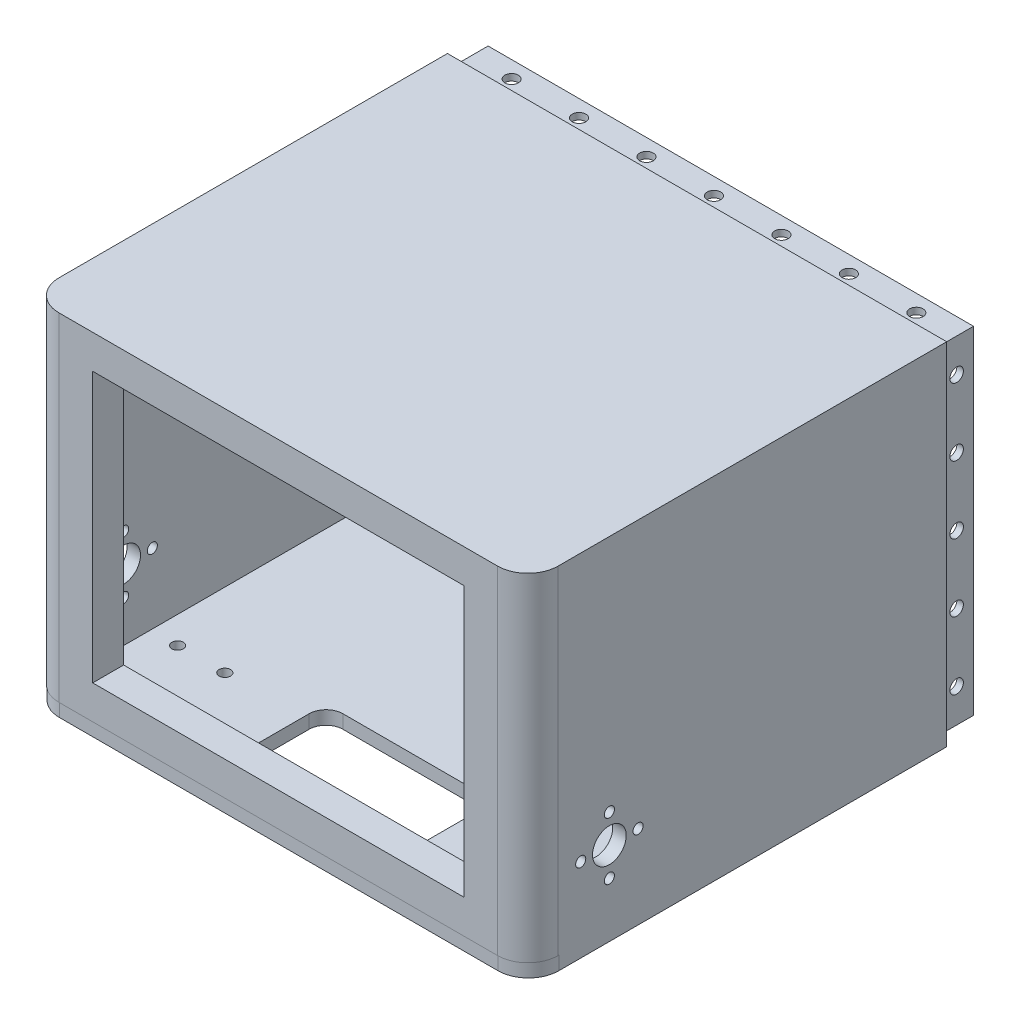
SolidWorks part; units mm, degrees
ref_plane "前视基准面" through (0, 0, 0) normal (0, 0, 1) x (1, 0, 0)
ref_plane "上视基准面" through (0, 0, 0) normal (0, 1, 0) x (1, 0, 0)
ref_plane "右视基准面" through (0, 0, 0) normal (1, 0, 0) x (0, 0, -1)
other "Configuration Table"
sketch "草图1" plane through (0, 0, 0) normal (0, 1, 0) x (1, 0, 0)
  line L0 (0, 120) -> (0, -49880) construction
  line L5 (-1000, 0) -> (49000, 0) construction
  line L6 (-25, -107.9892) -> (-25, -90)
  line L10 (-70, 115) -> (-70, 80)
  line L11 (20, -85) -> (-20, -85)
  line L12 (-70, 120) -> (-70, 113)
  line L13 (-70, 113) -> (-70, 87)
  line L14 (-70, 87) -> (-70, 80)
  line L15 (-70, 113) -> (-40, 113)
  line L16 (-40, 113) -> (-40, 87)
  line L17 (-40, 87) -> (-70, 87)
  line L18 (-70, 113) -> (-70, 108)
  line L19 (-70, 87) -> (-70, 92)
  line L20 (-40, 87) -> (-48, 87)
  line L21 (-48, 87) -> (-48, 92)
  line L22 (-48, 92) -> (-40, 92)
  line L23 (-70, 92) -> (-62, 92)
  line L24 (-62, 92) -> (-62, 87)
  line L25 (-70, 97.5) -> (-40, 97.5) construction
  line L26 (25, -107.9892) -> (25, -90)
  line L27 (25, -100) -> (25, -112.9892)
  line L28 (-70, 80) -> (0, 80)
  line L29 (-65, 120) -> (65, 120)
  line L30 (70, 115) -> (70, 80)
  line L31 (-65, -120) -> (65, -120)
  line L32 (70, -115) -> (70, -80)
  line L33 (-70, -115) -> (-70, -80)
  line L34 (20, 112.9892) -> (-20, 112.9892)
  line L36 (25, -85) -> (5, -85)
  line L38 (-25, 100) -> (-25, 90)
  line L39 (-20, 85) -> (-5, 85)
  line L43 (25, 100) -> (25, 90)
  line L44 (20, 85) -> (5, 85)
  line L46 (25, 100) -> (25, 107.9892)
  line L57 (25, -100) -> (25, -85)
  line L59 (0, 120) -> (0, 110)
  line L60 (-70, 80) -> (-70, -80)
  line L61 (70, -80) -> (70, 80)
  line L62 (25, 112.9892) -> (25, 85)
  line L63 (25, 85) -> (-25, 85)
  line L64 (-25, 107.9892) -> (-25, 85)
  line L65 (-25, -85) -> (-5, -85)
  line L66 (-25, -100) -> (-25, -85)
  line L67 (20, -112.9892) -> (-20, -112.9892)
  line L68 (-1001.7967, 0) -> (48998.2033, 0)
  line L69 (-74, 115) -> (-74, 80)
  line L70 (-65, 124) -> (65, 124)
  line L71 (74, 115) -> (74, 80)
  line L72 (74, -80) -> (74, 80)
  line L73 (74, -115) -> (74, -80)
  line L74 (-65, -124) -> (65, -124)
  line L75 (-74, -115) -> (-74, -80)
  line L76 (-74, 80) -> (-74, -80)
  circle A0 centre (-62, 92) radius 1.7
  circle A1 centre (-48, 92) radius 1.7
  circle A4 centre (48, 108) radius 1.7
  circle A5 centre (48, 92) radius 1.7
  circle A6 centre (62, 92) radius 1.7
  circle A7 centre (62, 108) radius 1.7
  circle A8 centre (62, -108) radius 1.7
  circle A9 centre (62, -92) radius 1.7
  circle A10 centre (48, -92) radius 1.7
  circle A11 centre (48, -108) radius 1.7
  circle A12 centre (-48, -92) radius 1.7
  circle A13 centre (-62, -92) radius 1.7
  circle A14 centre (-48, -108) radius 1.7
  circle A15 centre (-62, -108) radius 1.7
  arc A16 (20, 112.9892) -> (25, 107.9892) centre (20, 107.9892) cw
  arc A17 (25, 90) -> (20, 85) centre (20, 90) cw
  arc A18 (-20, 85) -> (-25, 90) centre (-20, 90) cw
  arc A19 (-25, 107.9892) -> (-20, 112.9892) centre (-20, 107.9892) cw
  arc A20 (20, -85) -> (25, -90) centre (20, -90) cw
  arc A21 (-20, -85) -> (-25, -90) centre (-20, -90) ccw
  arc A22 (-25, -107.9892) -> (-20, -112.9892) centre (-20, -107.9892) ccw
  arc A23 (20, -112.9892) -> (25, -107.9892) centre (20, -107.9892) ccw
  arc A24 (65, -120) -> (70, -115) centre (65, -115) ccw
  arc A25 (-70, -115) -> (-65, -120) centre (-65, -115) ccw
  arc A26 (65, 120) -> (70, 115) centre (65, 115) cw
  arc A27 (-70, 115) -> (-65, 120) centre (-65, 115) cw
  circle A28 centre (-62, 108) radius 1.7
  circle A29 centre (-48, 108) radius 1.7
  arc A30 (-74, 115) -> (-65, 124) centre (-65, 115) cw
  arc A31 (65, 124) -> (74, 115) centre (65, 115) cw
  arc A32 (65, -124) -> (74, -115) centre (65, -115) ccw
  arc A33 (-74, -115) -> (-65, -124) centre (-65, -115) ccw
  point P0 (0, 0)
  point P86 (-25, 112.9892)
  point P95 (-25, -112.9892)
  dimension "D12" = 3.4
  dimension "D13" = 3.4
  dimension "D3" = 5
  dimension "D4" = 40
  dimension "D5" = 7
  dimension "D6" = 7
  dimension "D7" = 30
  dimension "D8" = 5
  dimension "D9" = 5
  dimension "D10" = 8
  dimension "D11" = 8
  dimension "D14" = 4
  dimension "D15" = 15
  dimension "D16" = 8
  dimension "D17" = 20
  dimension "D22" = 10
extrude "凸台-拉伸6" add sketch "草图1" along normal blind 4
sketch "草图9" plane through (0, 4, 0) normal (0, 1, 0) x (1, 0, 0)
  line L1 (-74, 0) -> (74, 0)
  line L2 (-74, 0) -> (-74, -115.1666)
  line L3 (-65, -124.1666) -> (65, -124.1666)
  line L4 (74, 0) -> (74, -115.1666)
  arc A1 (65, -124.1666) -> (74, -115.1666) centre (65, -115.1666) ccw
  arc A2 (-65, -124.1666) -> (-74, -115.1666) centre (-65, -115.1666) cw
  dimension "D1" = 9
extrude "凸台-拉伸7" add sketch "草图9" along normal blind 100
sketch "草图10" plane through (0, 0, 0) normal (0, 0, -1) x (-1, 0, 0)
  line L0 (-70, 100) -> (-70, 4)
  line L1 (-74, 104) -> (74, 104)
  line L3 (-74, 0) -> (74, 0)
  line L4 (74, 104) -> (74, 0)
  line L5 (-70, 4) -> (70, 4)
  line L6 (70, 100) -> (70, 4)
  line L7 (-70, 100) -> (70, 100)
  line L8 (-74, 104) -> (-74, 0) construction
  dimension "D1" = 4
extrude "切除-拉伸20" cut sketch "草图10" against normal blind 115 contours L7 L0 L5 L6
sketch "草图13" plane through (0, 4, 0) normal (0, 1, 0) x (1, 0, 0)
  line L0 (-62, -92) -> (-62, -108) construction
  line L1 (-62, -100) -> (-74, -100)
  line L2 (-74, -115) -> (-74, -80) construction
sketch "草图16" plane through (-74, 0, 0) normal (-1, 0, 0) x (0, 0, 1)
  line L0 (0, 4) -> (100, 4)
  line L1 (0, 4) -> (115.1666, 4) construction
  line L2 (100, 4) -> (100, 24.75)
  line L3 (100, 24.75) -> (108.5, 24.75) construction
  circle A0 centre (100, 24.75) radius 4
  circle A1 centre (108.5, 24.75) radius 1.5
  circle A2 centre (100, 16.25) radius 1.5
  circle A3 centre (91.5, 24.75) radius 1.5
  circle A4 centre (100, 33.25) radius 1.5
  dimension "D3" = 8
  dimension "D5" = 3
  dimension "D1" = 100
  dimension "D2" = 20.75
  dimension "D4" = 8.5
  dimension "D6" = 4
extrude "切除-拉伸22" cut sketch "草图16" along normal through all both and the other way through all
sketch "草图21" plane through (0, 0, 124.1666) normal (0, 0, 1) x (1, 0, 0)
  line L0 (-55, 94) -> (-55, 14)
  line L1 (-65, 104) -> (65, 104)
  line L3 (-65, 4) -> (65, 4)
  line L4 (65, 104) -> (65, 4)
  line L5 (-55, 14) -> (55, 14)
  line L6 (55, 94) -> (55, 14)
  line L7 (-55, 94) -> (55, 94)
  line L8 (-65, 104) -> (-65, 4) construction
  dimension "D1" = 10
extrude "切除-拉伸28" cut sketch "草图21" against normal blind 50 contours L7 L0 L5 L6
sketch "草图22" plane through (0, 0, 0) normal (0, 0, -1) x (-1, 0, 0)
  line L0 (-72, 102) -> (-72, 2)
  line L1 (-74, 104) -> (74, 104)
  line L2 (-74, 104) -> (-74, 0)
  line L3 (-74, 0) -> (74, 0)
  line L4 (74, 104) -> (74, 0)
  line L5 (-72, 2) -> (72, 2)
  line L6 (72, 102) -> (72, 2)
  line L7 (-72, 102) -> (72, 102)
  dimension "D1" = 2
sketch "草图23" plane through (-74, 0, 0) normal (-1, 0, 0) x (0, 0, 1)
  circle A0 centre (100, 24.75) radius 5
  dimension "D1" = 10
extrude "切除-拉伸29" cut sketch "草图23" against normal through all
sketch "草图31" plane through (0, 0, 0) normal (0, 0, -1) x (-1, 0, 0)
  line L13 (-71.95, 101.95) -> (-71.95, 2.05)
  line L14 (-71.95, 2.05) -> (71.95, 2.05)
  line L15 (71.95, 2.05) -> (71.95, 101.95)
  line L16 (71.95, 101.95) -> (-71.95, 101.95)
  line L17 (-71.95, 101.95) -> (-71.95, 2.05)
  line L18 (-71.95, 2.05) -> (71.95, 2.05)
  line L19 (71.95, 2.05) -> (71.95, 101.95)
  line L20 (71.95, 101.95) -> (-71.95, 101.95)
  line L25 (-70, 100) -> (-70, 4)
  line L26 (-70, 4) -> (70, 4)
  line L27 (70, 4) -> (70, 100)
  line L28 (70, 100) -> (-70, 100)
  line L29 (-70, 100) -> (-70, 4)
  line L30 (-70, 4) -> (70, 4)
  line L31 (70, 4) -> (70, 100)
  line L32 (70, 100) -> (-70, 100)
  dimension "D1" = 0.05
  dimension "D2" = 2
extrude "凸台-拉伸9" add sketch "草图31" along normal blind 10
sketch "草图32" plane through (0, 101.95, 0) normal (0, 1, 0) x (1, 0, 0)
  line L0 (0, 10) -> (0, 5)
  line L1 (-71.95, 10) -> (71.95, 10) construction
  circle A0 centre (0, 5) radius 2
  circle A1 centre (20, 5) radius 2
  circle A2 centre (40, 5) radius 2
  circle A3 centre (60, 5) radius 2
  circle A4 centre (-60, 5) radius 2
  circle A5 centre (-20, 5) radius 2
  circle A6 centre (-40, 5) radius 2
  dimension "D2" = 4
  dimension "D1" = 5
  dimension "D3" = 4
extrude "切除-拉伸32" cut sketch "草图32" against normal through all both and the other way through all
sketch "草图33" plane through (-71.95, 0, 0) normal (-1, 0, 0) x (0, 0, 1)
  line L0 (-10, 52) -> (-5, 52)
  line L1 (-10, 2.05) -> (-10, 101.95) construction
  circle A0 centre (-5, 52) radius 2
  circle A1 centre (-5, 72) radius 2
  circle A2 centre (-5, 92) radius 2
  circle A3 centre (-5, 12) radius 2
  circle A4 centre (-5, 32) radius 2
  dimension "D2" = 4
  dimension "D1" = 5
  dimension "D3" = 3
extrude "切除-拉伸33" cut sketch "草图33" against normal through all both and the other way through all
